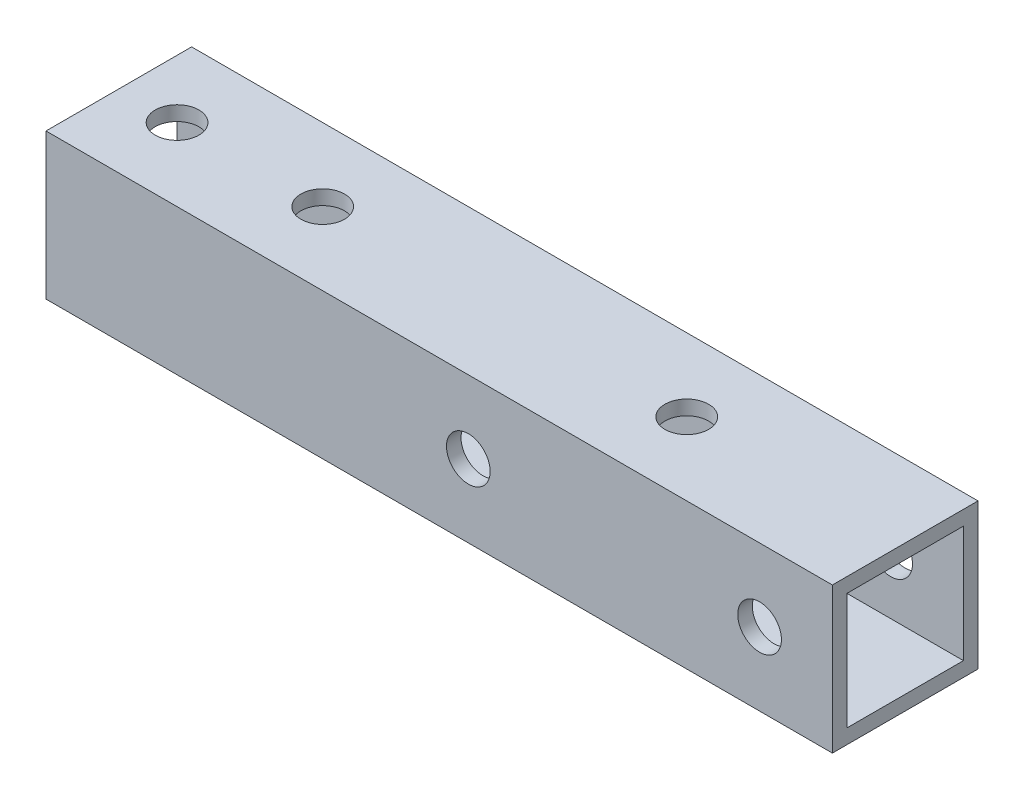
SolidWorks part; units mm, degrees
material "1060 合金"
ref_plane "正面" through (0, 0, 0) normal (0, 0, 1) x (1, 0, 0)
ref_plane "平面" through (0, 0, 0) normal (0, 1, 0) x (1, 0, 0)
ref_plane "右側面" through (0, 0, 0) normal (1, 0, 0) x (0, 0, -1)
sketch "ｽｹｯﾁ1" plane through (0, 0, 0) normal (1, 0, 0) x (0, 0, -1)
  line L1 (-5, -5) -> (5, -5)
  line L2 (-5, -5) -> (-5, 5)
  line L3 (-5, 5) -> (5, 5)
  line L4 (5, -5) -> (5, 5)
  line L5 (-5, -5) -> (5, 5) construction
  line L6 (-5, 5) -> (5, -5) construction
  point P0 (0, 0)
  dimension "D1" = 10
extrude "押し出し-薄板1" add sketch "ｽｹｯﾁ1" along normal blind 54 thin thin type one direction reverse wall 1
sketch "ｽｹｯﾁ2" plane through (0, 5, 0) normal (0, 1, 0) x (1, 0, 0)
  line L0 (0, 0) -> (54, 0) construction
  line L1 (0, 5) -> (0, -5) construction
  line L2 (54, 5) -> (54, -5) construction
  circle A0 centre (4, 0) radius 1.5
  circle A1 centre (14, 0) radius 1.5
  circle A2 centre (39, 0) radius 1.5
  dimension "D1" = 4
  dimension "D2" = 10
  dimension "D3" = 3
  dimension "D4" = 15
extrude "ｶｯﾄ - 押し出し1" cut sketch "ｽｹｯﾁ2" against normal through all
sketch "ｽｹｯﾁ3" plane through (0, 0, 5) normal (0, 0, 1) x (1, 0, 0)
  line L0 (0, 0) -> (54, 0) construction
  line L1 (54, 5) -> (54, -5) construction
  circle A1 centre (49, 0) radius 1.5
  circle A6 centre (29, 0) radius 1.5
  dimension "D1" = 3
  dimension "D2" = 5
  dimension "D3" = 20
extrude "ｶｯﾄ - 押し出し2" cut sketch "ｽｹｯﾁ3" against normal through all
